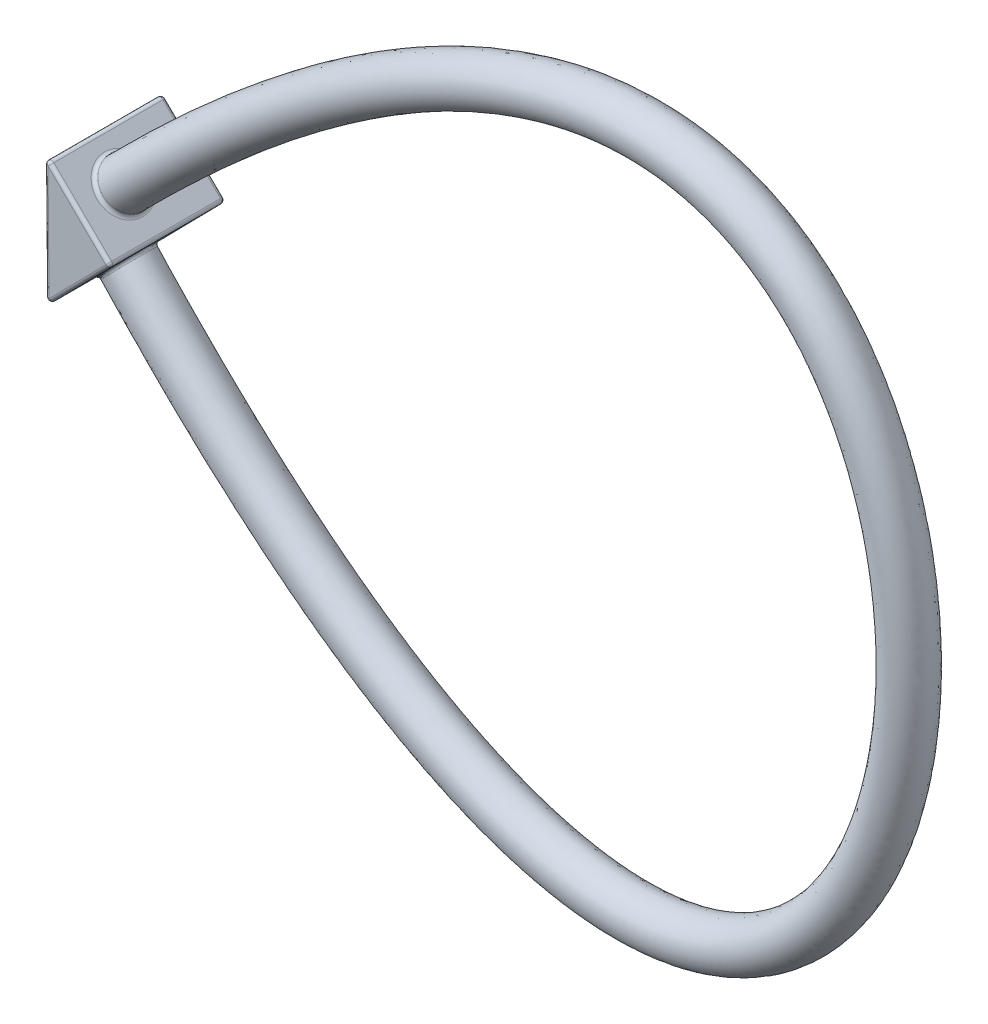
SolidWorks part; units mm, degrees
ref_plane "Front Plane" through (0, 0, 0) normal (0, 0, 1) x (1, 0, 0)
ref_plane "Top Plane" through (0, 0, 0) normal (0, 1, 0) x (1, 0, 0)
ref_plane "Right Plane" through (0, 0, 0) normal (1, 0, 0) x (0, 0, -1)
sketch "Sketch1" plane through (0, 0, 0) normal (0, 0, 1) x (1, 0, 0)
  spline S0 degree 3 poles (0, 0) (46.3756, 47.2258) (43.9685, -50.4898) (0, -2.5744) knots 0 0 0 0 1 1 1 1
ref_plane "Plane1" through (0, 0, 0) normal (0.7007, 0.7135, 0) x (0.7135, -0.7007, 0)
sketch "Sketch2" plane through (0, 0, 0) normal (0.7007, 0.7135, 0) x (0.7135, -0.7007, 0)
  circle A0 centre (0, 0) radius 1
  dimension "D1" = 2
sweep "Sweep1" add profiles "Sketch2" path "Sketch1"
sketch "Sketch3" plane through (0, 0, 0) normal (-0.7007, -0.7135, 0) x (0.7135, -0.7007, 0)
  line L1 (-2, -3) -> (2, -3)
  line L2 (-2, -3) -> (-2, 2)
  line L3 (-2, 2) -> (2, 2)
  line L4 (2, -3) -> (2, 2)
  dimension "D1" = 4
  dimension "D2" = 5
  dimension "D3" = 2
  dimension "D4" = 2
extrude "Boss-Extrude1" add sketch "Sketch3" along normal blind 4
sketch "Sketch4" plane through (0, 0, 2) normal (0, 0, 1) x (1, 0, 0)
  line L0 (-1.3756, -4.2553) -> (-1.427, 1.4013)
  line L1 (-1.3756, -4.2553) -> (-6.9578, -4.306)
  line L2 (-1.427, 1.4013) -> (-7.0092, 1.3506)
  line L3 (-6.9578, -4.306) -> (-7.0092, 1.3506)
extrude "Cut-Extrude1" cut sketch "Sketch4" against normal through all
fillet "Fillet1" radius 0.15 11 edges at (-1.4013, -1.427, -3) (0.0257, -2.8283, -3) (-1.3756, -4.2553, -0.5) (0.8157, -2.0238, 0.2299) (0, 0, -3) (1.427, -1.4013, -0.5) (-1.427, 1.4013, -0.5) (-0.7135, 0.7007, 0) (0.0257, -2.8283, 2) (-1.4013, -1.427, 2) (0, 0, 2)
